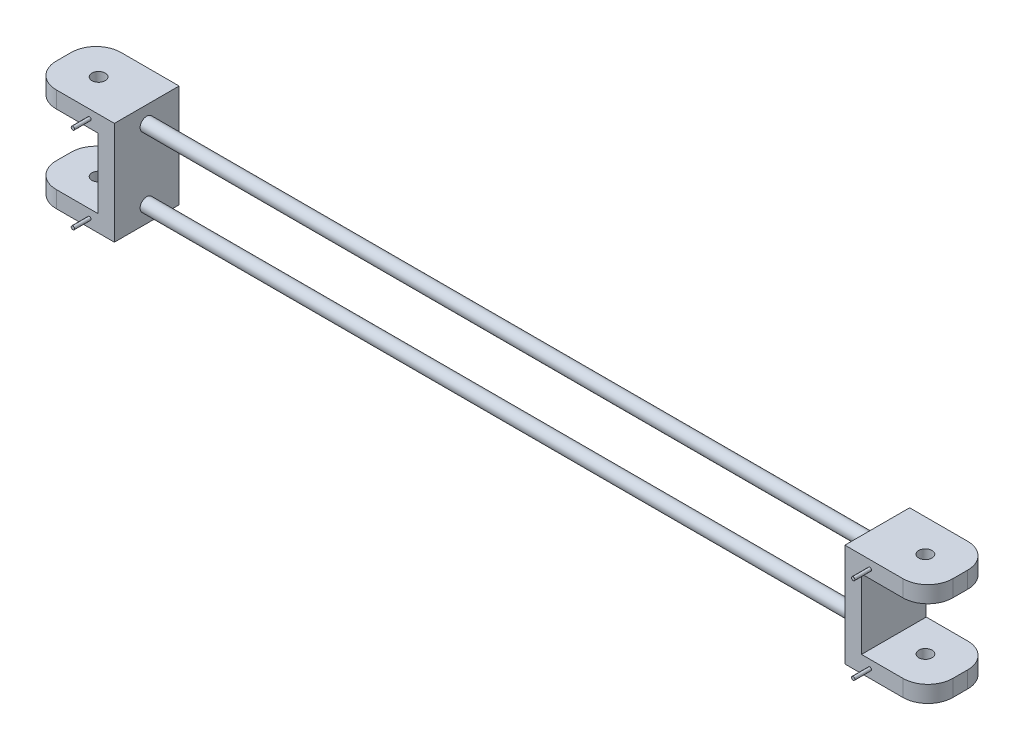
SolidWorks part; units mm, degrees
ref_plane "Plan de face" through (0, 0, 0) normal (0, 0, 1) x (1, 0, 0)
ref_plane "Plan de dessus" through (0, 0, 0) normal (0, 1, 0) x (1, 0, 0)
ref_plane "Plan de droite" through (0, 0, 0) normal (1, 0, 0) x (0, 0, -1)
sketch "Esquisse1" plane through (0, 0, 0) normal (0, 1, 0) x (1, 0, 0)
  line L1 (-270, -19.5) -> (270, -19.5)
  line L2 (-270, -19.5) -> (-270, 19.5)
  line L3 (-270, 19.5) -> (270, 19.5)
  line L4 (270, -19.5) -> (270, 19.5)
  line L5 (-270, -19.5) -> (270, 19.5) construction
  line L6 (-270, 19.5) -> (270, -19.5) construction
  point P0 (0, 0)
  dimension "D1" = 540
  dimension "D2" = 39
extrude "Boss.-Extru.1" add sketch "Esquisse1" along normal blind 10
fillet "Congé1" radius 15 4 edges at (270, 5, 19.5) (270, 5, -19.5) (-270, 5, 19.5) (-270, 5, -19.5)
sketch "Esquisse3" plane through (0, 10, 0) normal (0, 1, 0) x (1, 0, 0)
  line L0 (255, 19.5) -> (-255, 19.5) construction
  line L1 (-230, 19.5) -> (-220, 19.5)
  line L2 (-230, 19.5) -> (-230, -19.5)
  line L3 (-230, -19.5) -> (-220, -19.5)
  line L4 (-220, 19.5) -> (-220, -19.5)
  line L5 (-255, -19.5) -> (255, -19.5) construction
  line L6 (270, -4.5) -> (270, 4.5) construction
  line L7 (230, 19.5) -> (220, 19.5)
  line L8 (230, 19.5) -> (230, -19.5)
  line L9 (230, -19.5) -> (220, -19.5)
  line L10 (220, 19.5) -> (220, -19.5)
  line L11 (-270, 4.5) -> (-270, -4.5) construction
  dimension "D1" = 40
  dimension "D2" = 10
  dimension "D3" = 10
  dimension "D4" = 40
extrude "Boss.-Extru.2" add sketch "Esquisse3" along normal blind 42
sketch "Esquisse4" plane through (0, 52, 0) normal (0, 1, 0) x (1, 0, 0)
  line L0 (-220, -19.5) -> (220, -19.5) construction
  line L1 (-270, 4.5) -> (-270, -4.5) construction
  line L2 (-270, 19.5) -> (270, 19.5)
  line L3 (220, 19.5) -> (-220, 19.5) construction
  line L4 (-270, 19.5) -> (-270, -19.5)
  line L5 (-270, -19.5) -> (270, -19.5)
  line L6 (270, 19.5) -> (270, -19.5)
  line L7 (270, -4.5) -> (270, 4.5) construction
  dimension "D1" = 0
  dimension "D2" = 0
  dimension "D3" = 0
  dimension "D4" = 0
extrude "Boss.-Extru.3" add sketch "Esquisse4" along normal blind 10
fillet "Congé2" radius 15 4 edges at (-270, 57, -19.5) (270, 57, -19.5) (270, 57, 19.5) (-270, 57, 19.5)
sketch "Esquisse5" plane through (0, 62, 0) normal (0, 1, 0) x (1, 0, 0)
  line L0 (-249, -19.5) -> (-249, 19.5) construction
  line L1 (-255, -19.5) -> (255, -19.5) construction
  line L2 (255, 19.5) -> (-255, 19.5) construction
  line L3 (-249, 0) -> (-270, 0) construction
  line L4 (-270, 4.5) -> (-270, -4.5) construction
  line L5 (249, 19.5) -> (249, -19.5) construction
  line L6 (249, 0) -> (270, 0) construction
  line L7 (270, -4.5) -> (270, 4.5) construction
  circle A0 centre (249, 0) radius 4
  circle A1 centre (-249, 0) radius 4
  dimension "D3" = 8
  dimension "D4" = 8
  dimension "D1" = 21
  dimension "D2" = 21
extrude "Enlèv. mat.-Extru.2" cut sketch "Esquisse5" against normal through all both and the other way through all
sketch "Esquisse6" plane through (0, 0, 19.5) normal (0, 0, 1) x (1, 0, 0)
  line L7 (-230, 10) -> (-230, 0) construction
  line L8 (-255, 0) -> (255, 0) construction
  line L9 (-230, 57) -> (-240, 57) construction
  line L11 (230, 52) -> (230, 62) construction
  line L12 (-255, 62) -> (255, 62) construction
  line L13 (-230, 62) -> (-230, 52) construction
  line L14 (230, 10) -> (230, 0) construction
  line L16 (-230, 5) -> (-240, 5) construction
  line L19 (230, 57) -> (240, 57) construction
  line L21 (230, 5) -> (240, 5) construction
  circle A0 centre (-235, 57) radius 1
  circle A1 centre (-235, 5) radius 1
  circle A2 centre (235, 5) radius 1
  circle A3 centre (235, 57) radius 1
  dimension "D2" = 2
  dimension "D4" = 2
  dimension "D6" = 2
  dimension "D8" = 2
  dimension "D1" = 10
  dimension "D3" = 10
  dimension "D5" = 10
  dimension "D7" = 10
extrude "Boss.-Extru.4" add sketch "Esquisse6" along normal blind 10
sketch "Esquisse7" plane through (0, 0, 19.5) normal (0, 0, 1) x (1, 0, 0)
  line L0 (-255, 62) -> (255, 62) construction
  line L1 (-220, 62) -> (220, 62)
  line L2 (-220, 62) -> (-220, 52)
  line L3 (-220, 52) -> (220, 52)
  line L4 (220, 62) -> (220, 52)
  line L5 (-220, 52) -> (220, 52) construction
  line L6 (220, 52) -> (220, 10) construction
  line L7 (-220, 52) -> (-220, 10) construction
  dimension "D1" = 0
  dimension "D2" = 0
extrude "Enlèv. mat.-Extru.3" cut sketch "Esquisse7" against normal through all both and the other way through all
sketch "Esquisse13" plane through (0, 10, 0) normal (0, 1, 0) x (1, 0, 0)
  line L1 (-220, 19.5) -> (220, 19.5)
  line L2 (-220, 19.5) -> (-220, -19.5)
  line L3 (-220, -19.5) -> (220, -19.5)
  line L4 (220, 19.5) -> (220, -19.5)
extrude "Enlèv. mat.-Extru.4" cut sketch "Esquisse13" against normal through all both and the other way through all
sketch "Esquisse14" plane through (-220, 0, 0) normal (1, 0, 0) x (0, 0, -1)
  line L0 (0, 62) -> (0, 52) construction
  line L3 (19.5, 62) -> (-19.5, 62) construction
  line L4 (0, 0) -> (0, 10) construction
  line L5 (19.5, 0) -> (-19.5, 0) construction
  circle A0 centre (0, 52) radius 4
  circle A1 centre (0, 10) radius 4
  dimension "D3" = 8
  dimension "D4" = 8
  dimension "D1" = 10
  dimension "D2" = 10
extrude "Boss.-Extru.6" add sketch "Esquisse14" along normal up to next
